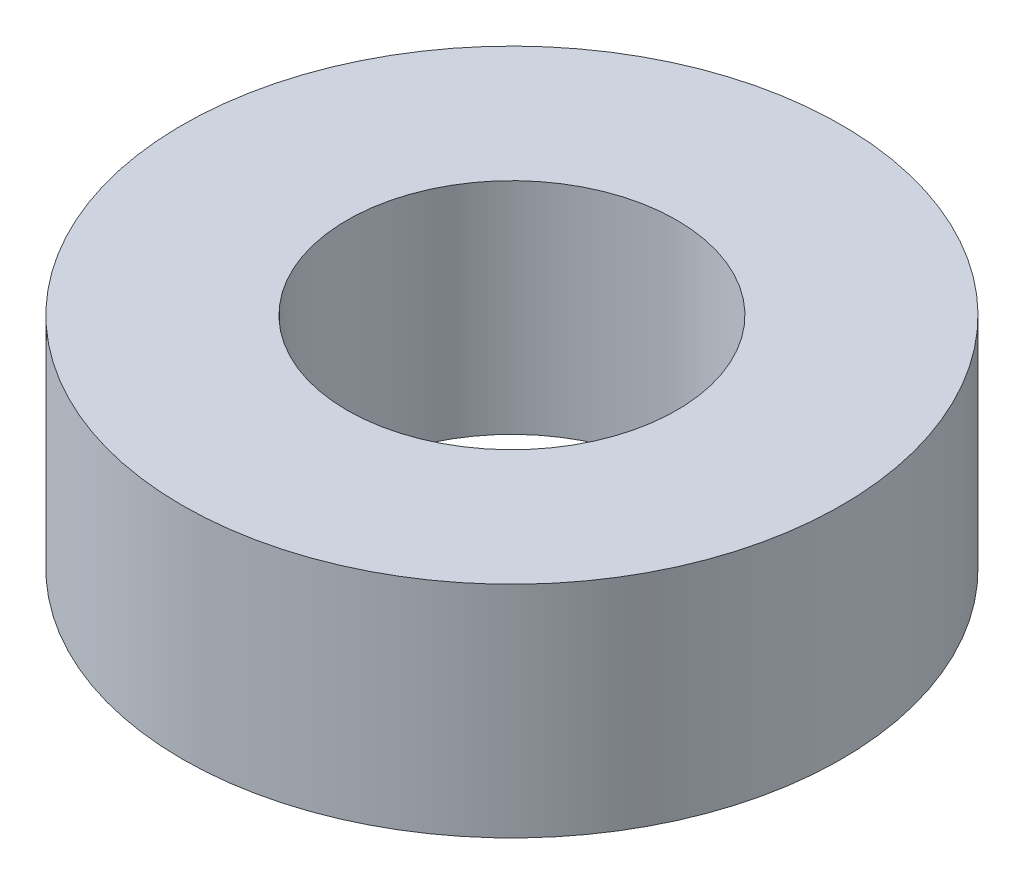
SolidWorks part; units mm, degrees
ref_plane "Front Plane" through (0, 0, 0) normal (0, 0, 1) x (1, 0, 0)
ref_plane "Top Plane" through (0, 0, 0) normal (0, 1, 0) x (1, 0, 0)
ref_plane "Right Plane" through (0, 0, 0) normal (1, 0, 0) x (0, 0, -1)
sketch "Sketch1" plane through (0, 0, 0) normal (0, 1, 0) x (1, 0, 0)
  circle A0 centre (0, 0) radius 4.7625
  circle A2 centre (0, 0) radius 2.3813
  point P5 (0, -0.2435)
  dimension "D1" = 4.7625
  dimension "D2" = 9.525
extrude "Boss-Extrude1" add sketch "Sketch1" along normal blind 3.175
